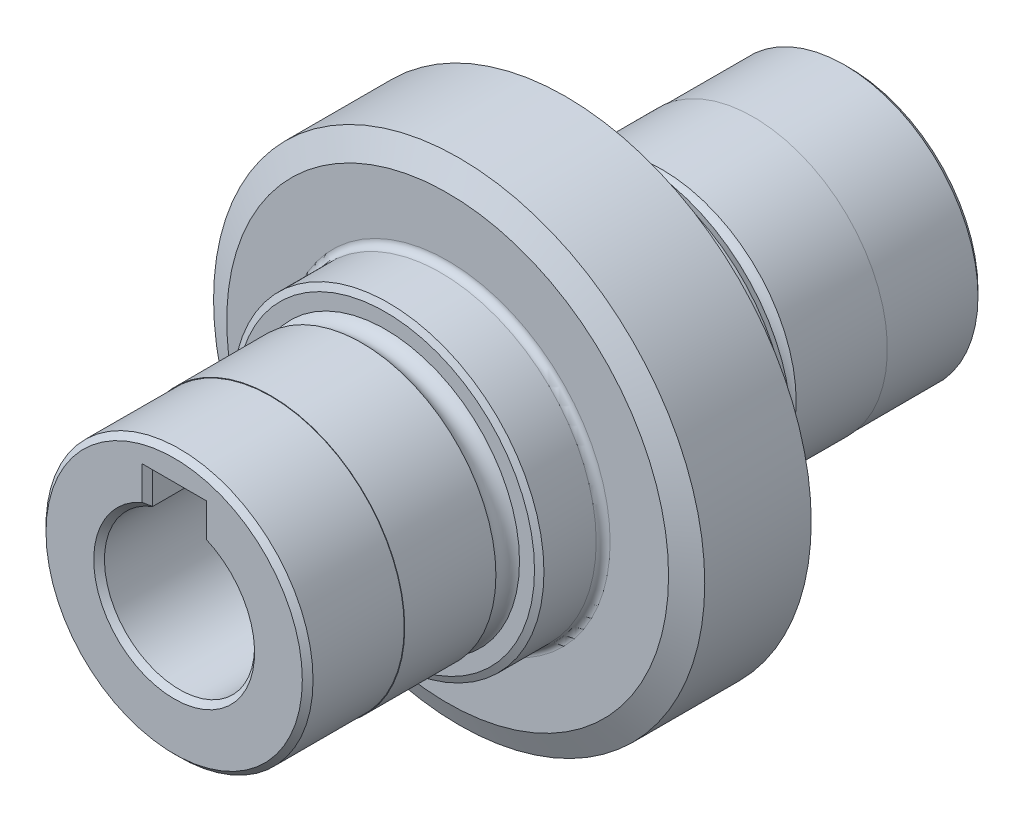
SolidWorks part; units mm, degrees
material "1.0038 (S235JRG2)"
ref_plane "Horní rovina" through (0, 0, 0) normal (0, 0, 1) x (1, 0, 0)
ref_plane "Přední rovina" through (0, 0, 0) normal (0, 1, 0) x (1, 0, 0)
ref_plane "Pravá rovina" through (0, 0, 0) normal (1, 0, 0) x (0, 0, -1)
sketch "Skica1" plane through (0, 0, 0) normal (0, 0, 1) x (1, 0, 0)
  circle A0 centre (0, 0) radius 22.9
  dimension "D1" = 45.8
extrude "Přidat vysunutím1" add sketch "Skica1" along normal mid plane 63
sketch "Skica2" plane through (0, 0, 31.5) normal (0, 0, 1) x (1, 0, 0)
  circle A0 centre (0, 0) radius 7
  dimension "D1" = 14
extrude "Odebrat vysunutím1" cut sketch "Skica2" against normal through all
sketch "Skica3" plane through (0, 0, 31.5) normal (0, 0, 1) x (1, 0, 0)
  line L0 (0, 0) -> (0, 7.5) construction
  line L1 (-2.5, 9.5) -> (2.5, 9.5)
  line L2 (-2.5, 9.5) -> (-2.5, 5.5)
  line L3 (-2.5, 5.5) -> (2.5, 5.5)
  line L4 (2.5, 9.5) -> (2.5, 5.5)
  line L5 (-2.5, 9.5) -> (2.5, 5.5) construction
  line L6 (-2.5, 5.5) -> (2.5, 9.5) construction
  point P0 (0, 7.5)
  dimension "D1" = 4
  dimension "D2" = 5
  dimension "D3" = 9.5
extrude "Odebrat vysunutím2" cut sketch "Skica3" against normal through all
sketch "Skica5" plane through (0, 0, -31.5) normal (0, 0, -1) x (-1, 0, 0)
  circle A0 centre (0, 0) radius 14.5
  circle A1 centre (0, 0) radius 22.9 construction
  circle A2 centre (0, 0) radius 22.9
  dimension "D1" = 29
extrude "Odebrat vysunutím4" cut sketch "Skica5" against normal blind 25.5
sketch "Skica6" plane through (0, 0, -31.5) normal (0, 0, -1) x (-1, 0, 0)
  circle A0 centre (0, 0) radius 12.5
  circle A1 centre (0, 0) radius 14.5
  circle A2 centre (0, 0) radius 14.5
  dimension "D2" = 25
  dimension "D1" = 0
extrude "Odebrat vysunutím5" cut sketch "Skica6" against normal blind 19.7
sketch "Skica7" plane through (0, 0, -31.5) normal (0, 0, -1) x (-1, 0, 0)
  circle A0 centre (0, 0) radius 12.45
  circle A1 centre (0, 0) radius 12.5
  circle A2 centre (0, 0) radius 12.5
  dimension "D1" = 0
  dimension "D2" = 0.05
extrude "Odebrat vysunutím6" cut sketch "Skica7" against normal blind 9
chamfer "Zkosení4" distance 0.6 angle 25 1 edges at (-14.5, 0, -11.8)
sketch "Skica8" plane through (0, 0, 0) normal (1, 0, 0) x (0, 0, -1)
  line L0 (11.8, -12.5) -> (11.8, 12.5) construction
  line L1 (11.8, -12.5) -> (11.8, 12.5) construction
  line L2 (11.8, -12.5) -> (15.2741, -12.5) construction
  line L3 (11.8, -12.5) -> (14, -12.5)
  line L4 (0, 0) -> (23.5967, 0) construction
  arc A0 (11.8, -12.5) -> (14, -12.5) centre (12.9, -13.1928) cw
  dimension "D1" = 2.2
  dimension "D2" = 1.3
revolve "Odebrat rotací1" cut sketch "Skica8" angle 360 about L4
mirror "Zrcadlit2" about plane through (0, 0, 0) normal (0, 0, 1) of "Odebrat rotací1", "Odebrat vysunutím6", "Odebrat vysunutím5", "Odebrat vysunutím4", "Zkosení4"
chamfer "Zkosení1" distance 0.5 angle 45 10 edges at (0, -7, -31.5) (0, -7, 31.5) (-2.5, 8.0192, -31.5) (0, 9.5, -31.5) (2.5, 8.0192, -31.5) (0, 9.5, 31.5) (-2.5, 8.0192, 31.5) (2.5, 8.0192, 31.5) (-12.45, 0, -31.5) (-12.45, 0, 31.5)
fillet "Zaoblit1" radius 0.65 2 edges at (-14.5, 0, 6) (-14.5, 0, -6)
chamfer "Zkosení2" distance 1 angle 66.5 1 edges at (-22.9, 0, -6)
chamfer "Zkosení3" distance 2.3 angle 25 1 edges at (-22.9, 0, 6)
